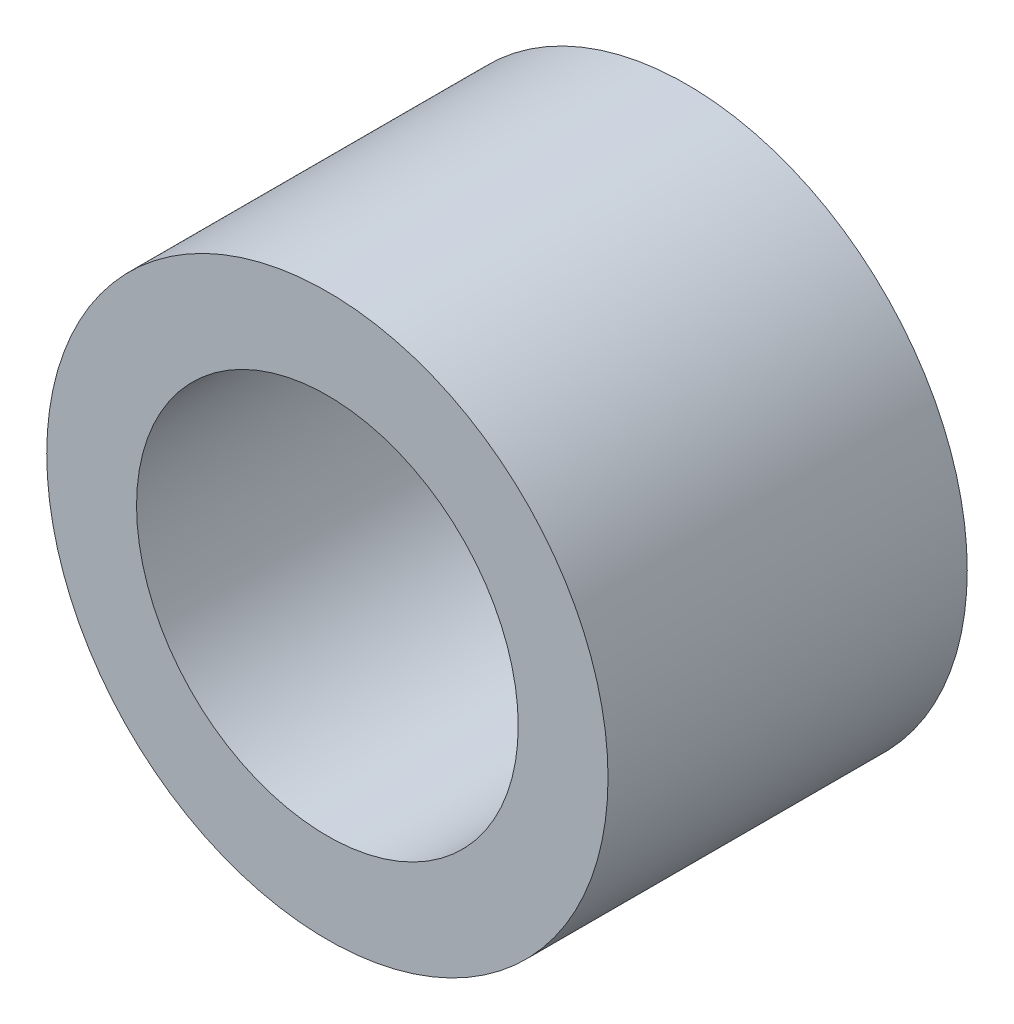
SolidWorks part; units mm, degrees
ref_plane "Спереди" through (0, 0, 0) normal (0, 0, 1) x (1, 0, 0)
ref_plane "Сверху" through (0, 0, 0) normal (0, 1, 0) x (1, 0, 0)
ref_plane "Справа" through (0, 0, 0) normal (1, 0, 0) x (0, 0, -1)
sketch "Эскиз1" plane through (0, 0, 0) normal (0, 0, 1) x (1, 0, 0)
  circle A0 centre (0, 0) radius 12.5
  circle A1 centre (0, 0) radius 8.5
extrude "Needle_bearing" add sketch "Эскиз1" along normal blind 16 from offset 47.5
